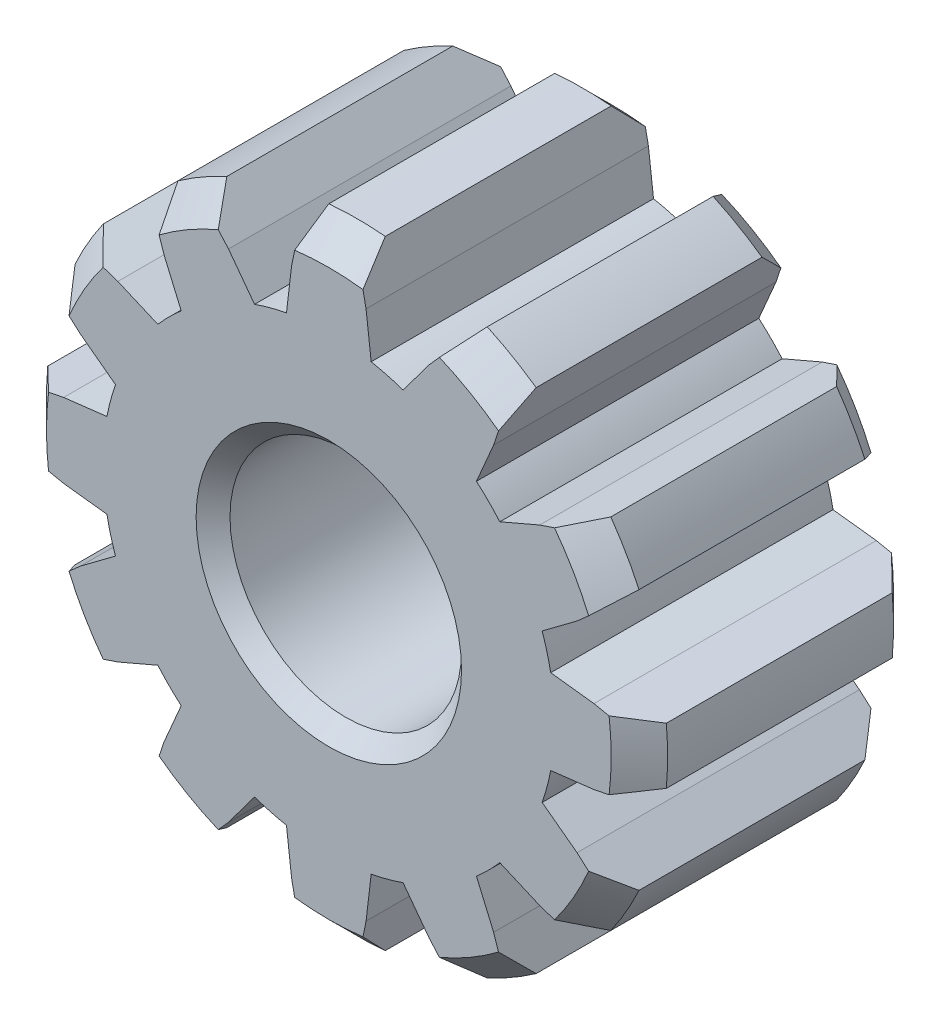
SolidWorks part; units mm, degrees
ref_plane "정면" through (0, 0, 0) normal (0, 0, 1) x (1, 0, 0)
ref_plane "윗면" through (0, 0, 0) normal (0, 1, 0) x (1, 0, 0)
ref_plane "우측면" through (0, 0, 0) normal (1, 0, 0) x (0, 0, -1)
sketch "스케치1" plane through (0, 0, 0) normal (0, 0, 1) x (1, 0, 0)
  line L0 (0, 0) -> (0, 5.5) construction
  line L1 (-0.5, 5.4772) -> (-0.6594, 4.695)
  line L2 (-0.6594, 4.695) -> (-0.75, 3.9291)
  line L3 (0.6594, 4.695) -> (0.75, 3.9291)
  line L4 (0.5, 5.4772) -> (0.6594, 4.695)
  circle A0 centre (0, 0) radius 4
  circle A1 centre (0, 0) radius 2.05
  arc A2 (0.5, 5.4772) -> (-0.5, 5.4772) centre (0, 0) ccw
  dimension "D1" = 4.1
  dimension "D2" = 8
  dimension "D5" = 5.5
  dimension "D3" = 1
  dimension "D4" = 1.5
extrude "보스-돌출1" add sketch "스케치1" along normal mid plane 5
pattern_circular "원형 패턴1" count 12 every 30 about axis through (0, 0, 0) along (0, 0, 1) of "보스-돌출1"
chamfer "모따기1" distance 0.5 angle 45 12 edges at (0, 5.5, -2.5) (-2.75, 4.7631, -2.5) (-4.7631, 2.75, -2.5) (-5.5, 0, -2.5) (-4.7631, -2.75, -2.5) (-2.75, -4.7631, -2.5) (0, -5.5, -2.5) (2.75, -4.7631, -2.5) (4.7631, -2.75, -2.5) (5.5, 0, -2.5) (4.7631, 2.75, -2.5) (2.75, 4.7631, -2.5)
chamfer "모따기2" distance 0.5 angle 45 12 edges at (0, 5.5, 2.5) (2.75, 4.7631, 2.5) (4.7631, 2.75, 2.5) (5.5, 0, 2.5) (4.7631, -2.75, 2.5) (2.75, -4.7631, 2.5) (0, -5.5, 2.5) (-2.75, -4.7631, 2.5) (-4.7631, -2.75, 2.5) (-5.5, 0, 2.5) (-4.7631, 2.75, 2.5) (-2.75, 4.7631, 2.5)
chamfer "모따기3" distance 0.3 angle 45 2 edges at (2.05, 0, 2.5) (2.05, 0, -2.5)
